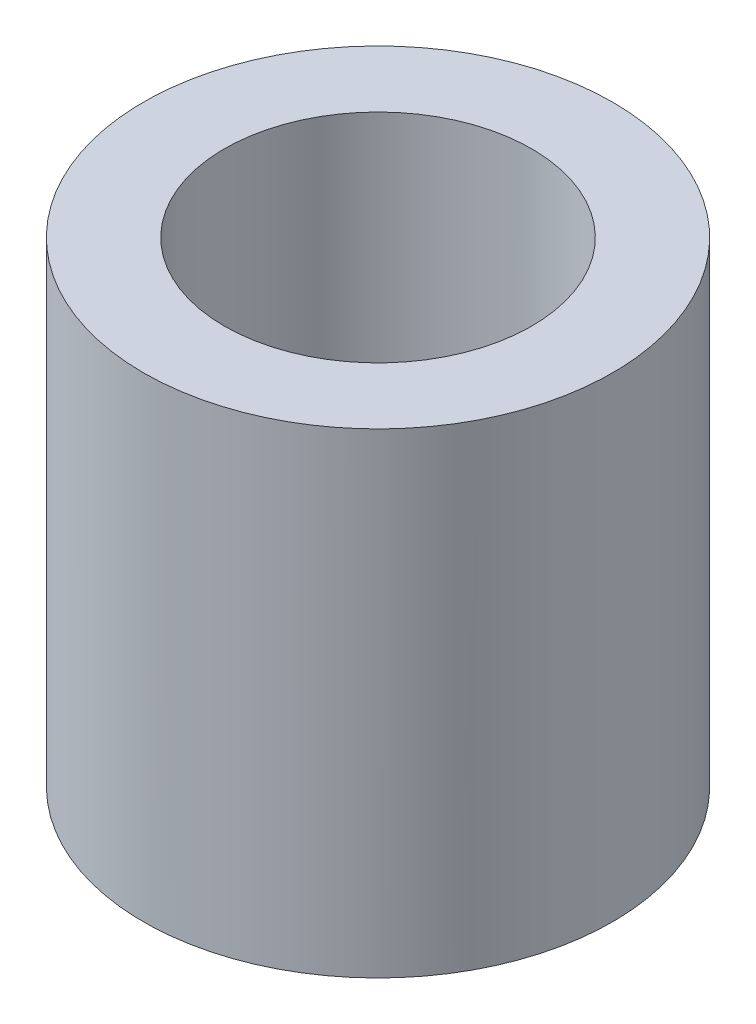
SolidWorks part; units mm, degrees
ref_plane "Front Plane" through (0, 0, 0) normal (0, 0, 1) x (1, 0, 0)
ref_plane "Top Plane" through (0, 0, 0) normal (0, 1, 0) x (1, 0, 0)
ref_plane "Right Plane" through (0, 0, 0) normal (1, 0, 0) x (0, 0, -1)
sketch "Sketch1" plane through (0, 0, 0) normal (0, 1, 0) x (1, 0, 0)
  circle A0 centre (0, 0) radius 29
  circle A1 centre (0, 0) radius 19
  dimension "D1" = 58
  dimension "D2" = 10
extrude "Boss-Extrude1" add sketch "Sketch1" along normal blind 58.8
sketch "Sketch2" plane through (0, 0, 0) normal (0, 0, 1) x (1, 0, 0)
  circle A1 centre (0, 0) radius 10.45
  dimension "D2" = 20.9
extrude "Cut-Extrude1" cut sketch "Sketch2" against normal through all
